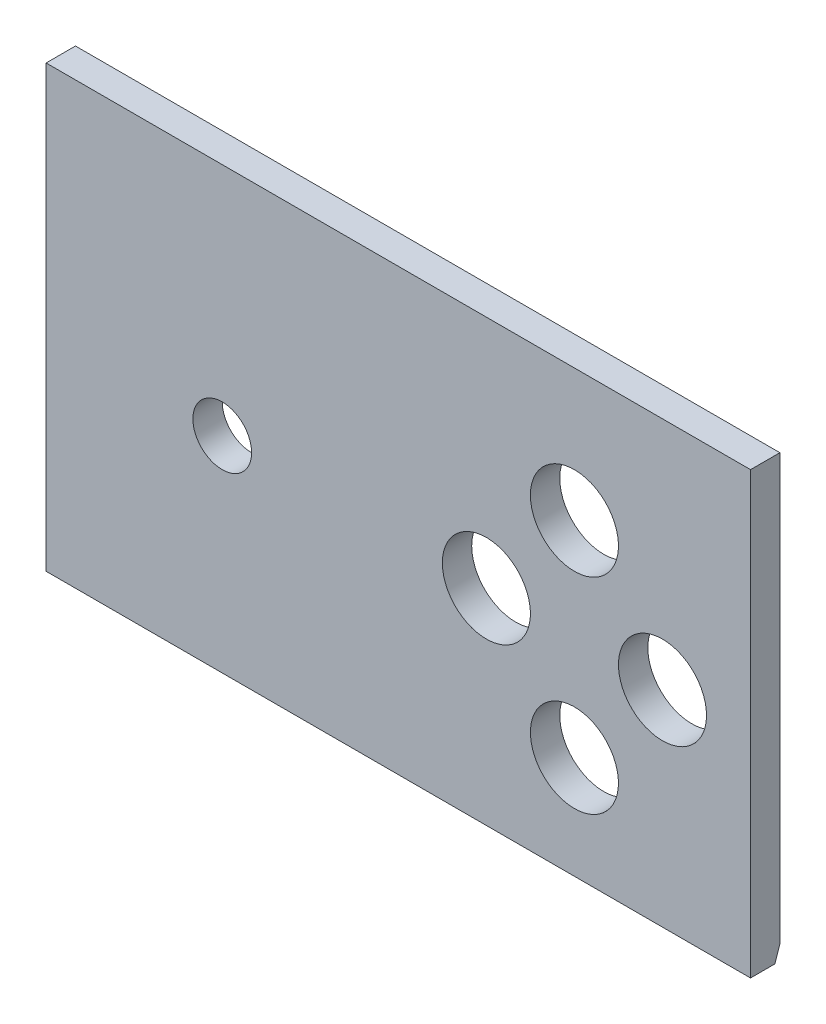
SolidWorks part; units mm, degrees
ref_plane "Alzado" through (0, 0, 0) normal (0, 0, 1) x (1, 0, 0)
ref_plane "Planta" through (0, 0, 0) normal (0, 1, 0) x (1, 0, 0)
ref_plane "Vista lateral" through (0, 0, 0) normal (1, 0, 0) x (0, 0, -1)
sketch "Croquis2" plane through (0, 0, 0) normal (0, 0, 1) x (1, 0, 0)
  line L0 (0, 150) -> (0, 140) construction
  line L1 (0, 0) -> (240, 0)
  line L2 (0, 0) -> (0, 150)
  line L3 (0, 150) -> (240, 150)
  line L4 (240, 0) -> (240, 150)
  line L5 (0, 140) -> (240, 140) construction
  line L6 (120, 0) -> (120, 140) construction
  line L7 (120, 70) -> (0, 70) construction
  line L9 (240, 70) -> (180, 70) construction
  line L10 (180, 70) -> (180, 0) construction
  circle A0 centre (60, 70) radius 10
  circle A1 centre (180, 35) radius 15
  circle A2 centre (210, 70) radius 15
  circle A3 centre (150, 70) radius 15
  circle A4 centre (180, 105) radius 15
extrude "Saliente-Extruir2" add sketch "Croquis2" along normal blind 10
sketch "Croquis4" plane through (240, 0, 0) normal (1, 0, 0) x (0, 0, -1)
  line L0 (-0.0255, 4.9434) -> (-1.6797, 0)
  line L1 (-10, 0) -> (0, 0) construction
  line L2 (-0.0255, 4.9434) -> (-3.1988, -4.5398) construction
  line L3 (-1.6797, 0) -> (0, 0)
  line L4 (0, 0) -> (-0.0255, 4.9434)
extrude "Cortar-Extruir1" cut sketch "Croquis4" against normal blind 240
ref_plane "Plano1" through (240, 0, 0) normal (0, 1, 0) x (1, 0, 0)
sketch "Croquis6" plane through (240, 0, 0) normal (1, 0, 0) x (0, 0, -1)
  line L0 (-0.0255, 4.9434) -> (0, 4.9348)
  line L1 (0, 0) -> (0, 150) construction
  line L2 (-0.0255, 4.9434) -> (142.9143, -42.8866) construction
  line L3 (0, 4.9348) -> (0, -0.0703)
  line L4 (0, -0.0703) -> (-0.0128, -0.0703)
  line L5 (-0.0255, 4.9434) -> (-0.0128, -0.0703)
extrude "Cortar-Extruir2" cut sketch "Croquis6" against normal blind 240
